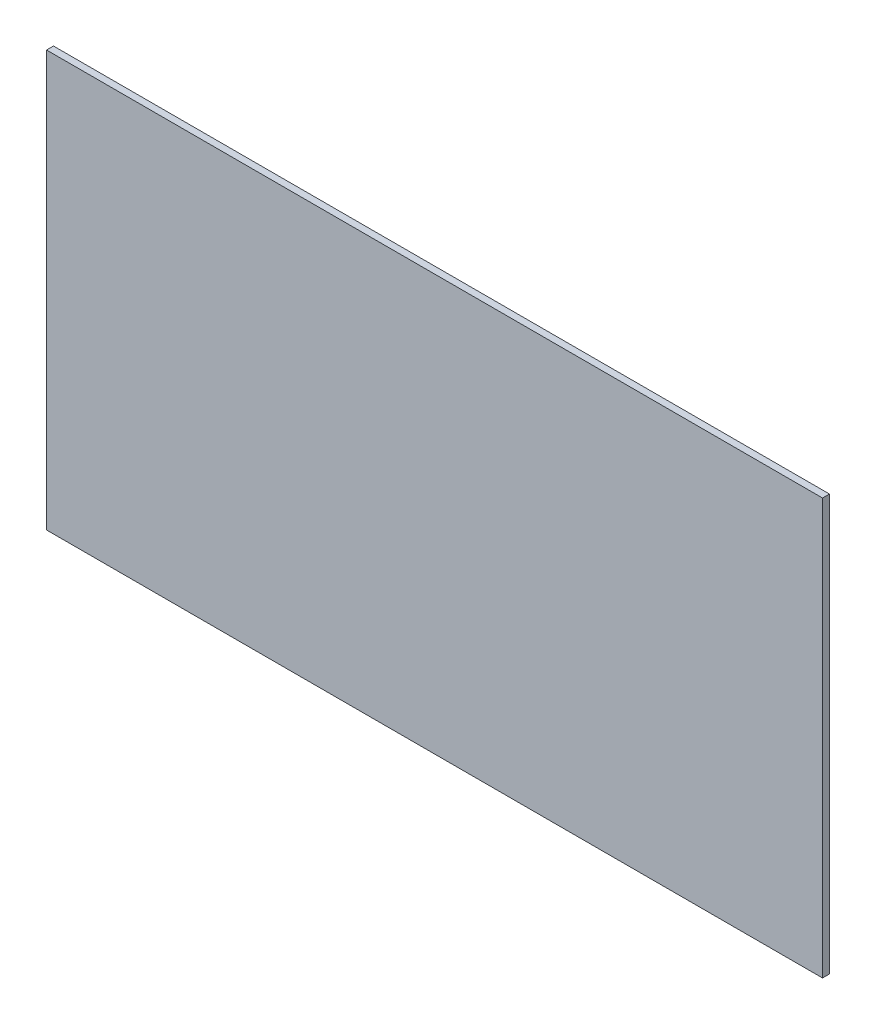
SolidWorks part; units mm, degrees
material "Acrilico (impatto medio-alto)"
ref_plane "Piano frontale" through (0, 0, 0) normal (0, 0, 1) x (1, 0, 0)
ref_plane "Piano superiore" through (0, 0, 0) normal (0, 1, 0) x (1, 0, 0)
ref_plane "Piano destro" through (0, 0, 0) normal (1, 0, 0) x (0, 0, -1)
sketch "Schizzo1" plane through (0, 0, 0) normal (0, 0, 1) x (1, 0, 0)
  line L1 (0, 0) -> (280, 0)
  line L3 (0, 150) -> (280, 150)
  line L14 (0, 0) -> (0, 150)
  line L15 (280, 0) -> (280, 150)
  dimension "D1" = 150
  dimension "D2" = 280
extrude "Estrusione-Estrusione1" add sketch "Schizzo1" along normal blind 2.5
